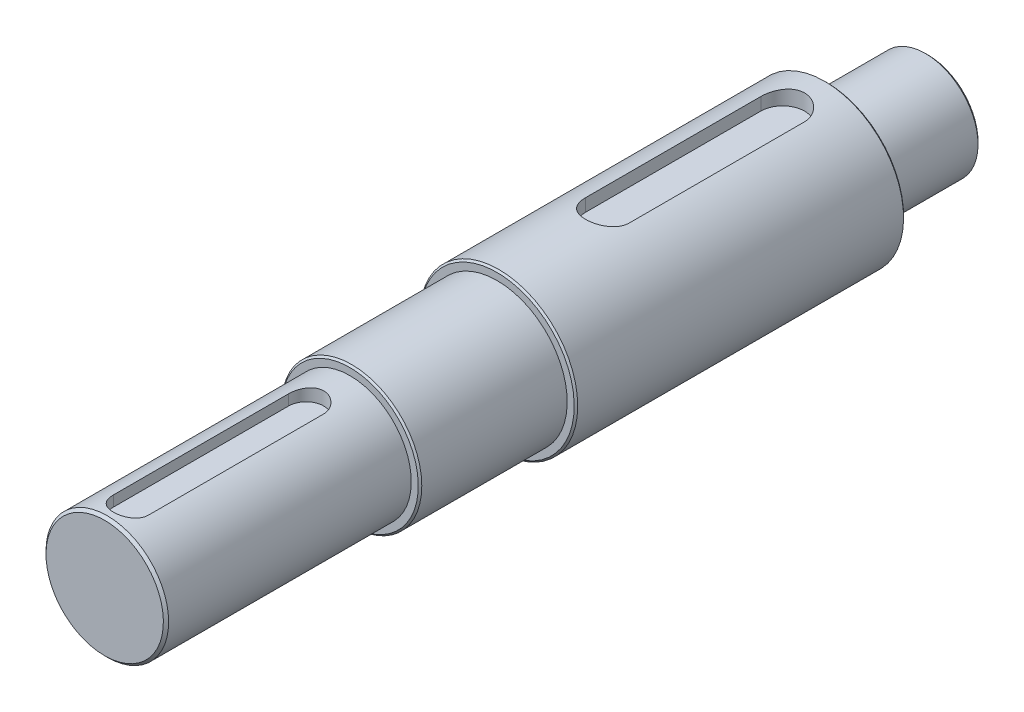
SolidWorks part; units mm, degrees
ref_plane "Front Plane" through (0, 0, 0) normal (0, 0, 1) x (1, 0, 0)
ref_plane "Top Plane" through (0, 0, 0) normal (0, 1, 0) x (1, 0, 0)
ref_plane "Right Plane" through (0, 0, 0) normal (1, 0, 0) x (0, 0, -1)
sketch "Sketch1" plane through (0, 0, 0) normal (1, 0, 0) x (0, 0, -1)
  line L0 (0, 0) -> (0, 35)
  line L1 (0, 35) -> (140, 35)
  line L2 (140, 35) -> (140, 40)
  line L3 (140, 40) -> (224, 40)
  line L4 (224, 40) -> (224, 45)
  line L5 (224, 45) -> (412, 45)
  line L6 (412, 45) -> (412, 30)
  line L7 (412, 30) -> (470, 30)
  line L8 (470, 30) -> (470, 0)
  line L9 (470, 0) -> (0, 0)
  dimension "D1" = 470
  dimension "D2" = 140
  dimension "D3" = 84
  dimension "D4" = 188
  dimension "D5" = 35
  dimension "D6" = 40
  dimension "D7" = 45
  dimension "D8" = 30
revolve "Revolve1" add sketch "Sketch1" angle 360 about L9
sketch "Sketch2" plane through (0, 0, 0) normal (0, 1, 0) x (1, 0, 0)
  line L0 (0, 15) -> (0, 115) construction
  line L1 (-10, 15) -> (-10, 115)
  line L2 (10, 15) -> (10, 115)
  arc A0 (-10, 15) -> (10, 15) centre (0, 15) ccw
  arc A1 (10, 115) -> (-10, 115) centre (0, 115) ccw
  point P3 (0, 65)
  point P8 (0, 0)
  dimension "D2" = 10
  dimension "D1" = 15
  dimension "D3" = 100
extrude "Cut-Extrude1" cut sketch "Sketch2" along normal blind 10 from offset 27.5
sketch "Sketch4" plane through (0, 0, 0) normal (0, 1, 0) x (1, 0, 0)
  line L0 (0, 387) -> (0, 287) construction
  line L1 (12.5, 387) -> (12.5, 287)
  line L2 (-12.5, 387) -> (-12.5, 287)
  line L3 (45, 412) -> (-45, 412) construction
  arc A0 (12.5, 387) -> (-12.5, 387) centre (0, 387) ccw
  arc A1 (-12.5, 287) -> (12.5, 287) centre (0, 287) ccw
  point P3 (0, 337)
  dimension "D1" = 12.5
  dimension "D2" = 25
  dimension "D3" = 100
extrude "Cut-Extrude2" cut sketch "Sketch4" along normal blind 10 from offset 36
chamfer "Chamfer1" distance 1.5 angle 45 2 edges at (0, 35, 0) (0, 30, -470)
chamfer "Chamfer2" distance 1 angle 45 3 edges at (0, 45, -412) (0, 40, -140) (0, 45, -224)
